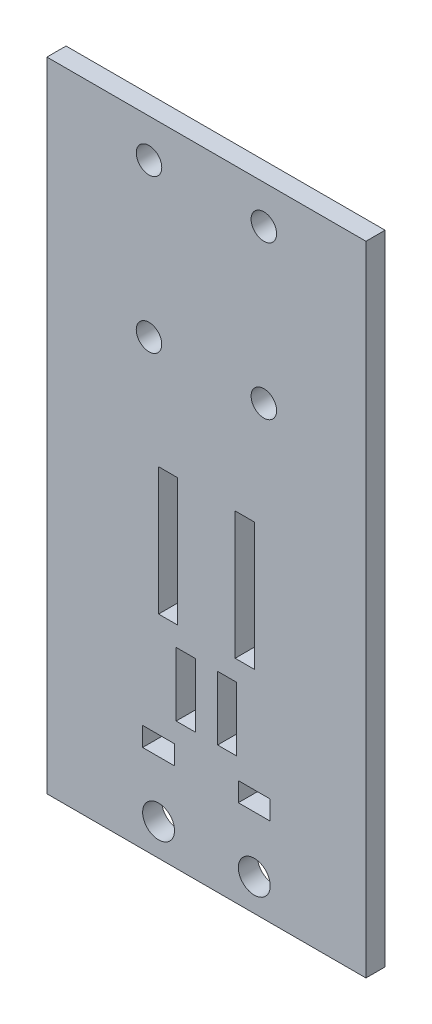
SolidWorks part; units mm, degrees
ref_plane "Front Plane" through (0, 0, 0) normal (0, 0, 1) x (1, 0, 0)
ref_plane "Top Plane" through (0, 0, 0) normal (0, 1, 0) x (1, 0, 0)
ref_plane "Right Plane" through (0, 0, 0) normal (1, 0, 0) x (0, 0, -1)
sketch "Sketch1" plane through (0, 0, 0) normal (0, 0, 1) x (1, 0, 0)
  line L0 (0, -50) -> (0, 50) construction
  line L1 (25, -50) -> (-25, -50)
  line L2 (25, -50) -> (25, 50)
  line L3 (25, 50) -> (-25, 50)
  line L4 (-25, -50) -> (-25, 50)
  line L5 (25, -50) -> (-25, 50) construction
  line L6 (25, 50) -> (-25, -50) construction
  line L7 (-25, 32) -> (25, 32) construction
  line L16 (4.5, -16.8518) -> (7.5, -16.8518)
  line L17 (7.5, -16.8518) -> (7.5, 3.1482)
  line L18 (-4.5, -16.8518) -> (-7.5, -16.8518)
  line L19 (-4.5, -16.8518) -> (-4.5, 3.1482)
  line L20 (-4.5, 3.1482) -> (-7.5, 3.1482)
  line L21 (-7.5, -16.8518) -> (-7.5, 3.1482)
  line L22 (-4.5, -16.8518) -> (-7.5, 3.1482) construction
  line L23 (-4.5, 3.1482) -> (-7.5, -16.8518) construction
  line L24 (4.5, -16.8518) -> (4.5, 3.1482)
  line L25 (4.5, 3.1482) -> (7.5, 3.1482)
  circle A0 centre (-9, 44) radius 2
  circle A1 centre (9, 44) radius 2
  circle A2 centre (-9, 20) radius 2
  circle A3 centre (9, 20) radius 2
  circle A6 centre (-7.5, -45) radius 2.5
  circle A8 centre (7.5, -45) radius 2.5
  point P0 (0, 0)
  point P18 (-4.0078, -37.5)
  point P20 (-6, -6.8518)
  dimension "D3" = 18
  dimension "4" = 4
  dimension "D6" = 3
  dimension "D7" = 20
  dimension "D10" = 5
  dimension "D11" = 15
  dimension "D1" = 50
  dimension "D2" = 100
  dimension "D4" = 24
  dimension "D5" = 6
  dimension "D15" = 5
  dimension "30" = 12
extrude "Boss-Extrude1" add sketch "Sketch1" along normal blind 3
sketch "Sketch2" plane through (0, 0, 3) normal (0, 0, 1) x (1, 0, 0)
  line L0 (0, 50) -> (0, -50) construction
  line L1 (-25, -50) -> (25, -50) construction
  line L2 (25, 50) -> (-25, 50) construction
  line L3 (4.75, -30) -> (1.75, -30)
  line L4 (-4.75, -20) -> (-1.75, -20)
  line L5 (-4.75, -20) -> (-4.75, -30)
  line L6 (-4.75, -30) -> (-1.75, -30)
  line L7 (-1.75, -20) -> (-1.75, -30)
  line L8 (-4.75, -20) -> (-1.75, -30) construction
  line L9 (-4.75, -30) -> (-1.75, -20) construction
  line L10 (4.75, -20) -> (4.75, -30)
  line L11 (1.75, -20) -> (1.75, -30)
  line L12 (4.75, -20) -> (1.75, -20)
  point P7 (-3.25, -25)
  dimension "D1" = 70
  dimension "10" = 10
  dimension "3" = 3
  dimension "D2" = 3.5
extrude "Cut-Extrude1" cut sketch "Sketch2" against normal blind 10
sketch "Sketch3" plane through (0, 0, 3) normal (0, 0, 1) x (1, 0, 0)
  line L0 (0, 50) -> (0, -50) construction
  line L1 (25, 50) -> (-25, 50) construction
  line L2 (-5, -36.2096) -> (-10, -36.2096)
  line L3 (-5, -36.2096) -> (-5, -33.2096)
  line L4 (-5, -33.2096) -> (-10, -33.2096)
  line L5 (-10, -36.2096) -> (-10, -33.2096)
  line L6 (-5, -36.2096) -> (-10, -33.2096) construction
  line L7 (-5, -33.2096) -> (-10, -36.2096) construction
  line L8 (-25, -50) -> (25, -50) construction
  line L9 (10, -36.2096) -> (10, -33.2096)
  line L10 (5, -33.2096) -> (10, -33.2096)
  line L11 (5, -36.2096) -> (5, -33.2096)
  line L12 (5, -36.2096) -> (10, -36.2096)
  point P1 (-7.5, -34.7096)
  dimension "D1" = 3
  dimension "D2" = 5
  dimension "D3" = 10
extrude "Cut-Extrude2" cut sketch "Sketch3" against normal through all
